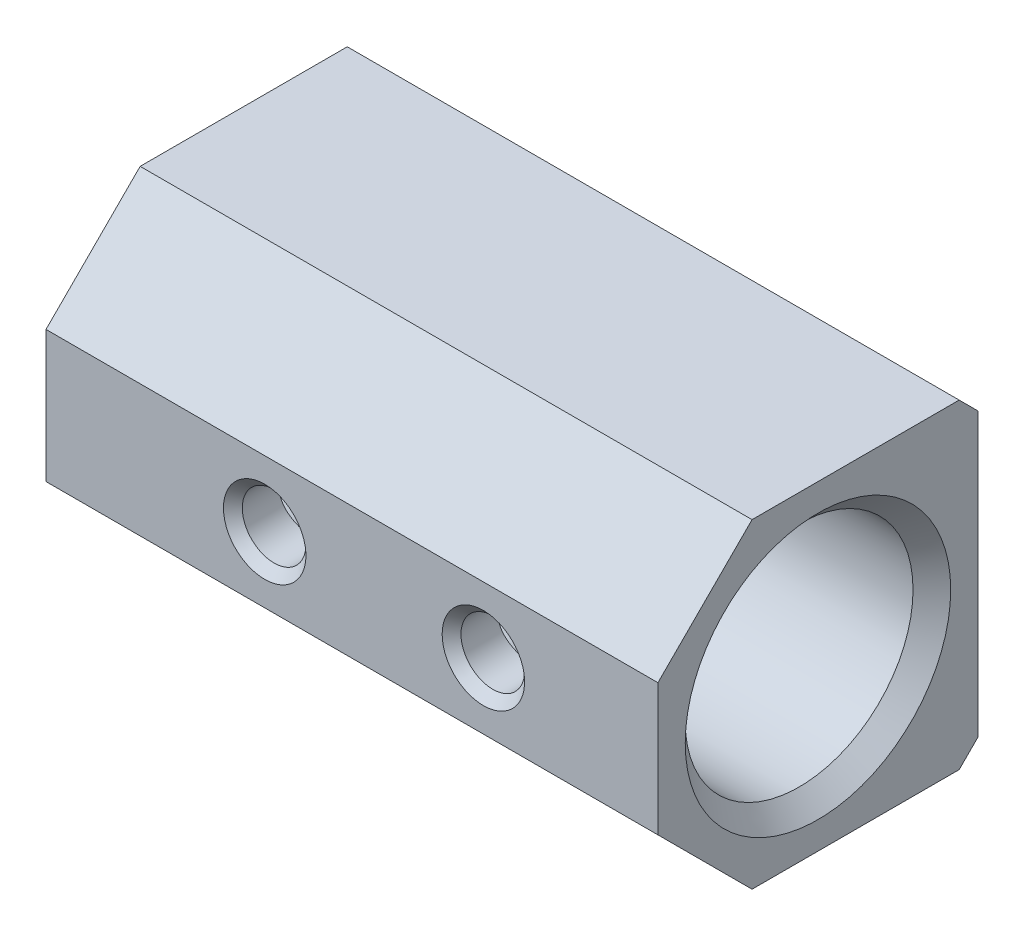
SolidWorks part; units mm, degrees
ref_plane "Front Plane" through (0, 0, 0) normal (0, 0, 1) x (1, 0, 0)
ref_plane "Top Plane" through (0, 0, 0) normal (0, 1, 0) x (1, 0, 0)
ref_plane "Right Plane" through (0, 0, 0) normal (1, 0, 0) x (0, 0, -1)
sketch "Sketch2" plane through (0, 0, 0) normal (0, 0, 1) x (1, 0, 0)
  line L1 (-32.5, -17) -> (32.5, -17)
  line L2 (-32.5, -17) -> (-32.5, 17)
  line L3 (-32.5, 17) -> (32.5, 17)
  line L4 (32.5, -17) -> (32.5, 17)
  line L5 (-32.5, -17) -> (32.5, 17) construction
  line L6 (-32.5, 17) -> (32.5, -17) construction
  point P0 (0, 0)
  dimension "D1" = 34
  dimension "D2" = 65
extrude "Boss-Extrude1" add sketch "Sketch2" along normal blind 34
chamfer "Chamfer1" distance 10 angle 45 2 edges at (0, 17, 34) (0, -17, 34)
chamfer "Chamfer2" distance 2 angle 45 2 edges at (0, 17, 0) (0, -17, 0)
sketch "Sketch3" plane through (32.5, 0, 0) normal (1, 0, 0) x (0, 0, -1)
  line L0 (0, -15) -> (0, 15) construction
  line L1 (-24, 17) -> (-2, 17) construction
  circle A0 centre (-17, 0) radius 12.1
  dimension "D1" = 24.2
  dimension "D2" = 17
  dimension "D3" = 17
extrude "Cut-Extrude1" cut sketch "Sketch3" against normal through all
chamfer "Chamfer3" distance 2 angle 45 1 edges at (32.5, 0, 4.9)
sketch "Sketch4" plane through (0, 0, 34) normal (0, 0, 1) x (1, 0, 0)
  line L0 (-32.5, 7) -> (-32.5, -7) construction
  circle A0 centre (-9.27, 0) radius 3.38
  circle A1 centre (13.96, 0) radius 3.38
  point P6 (0, 0)
  point P8 (0, 0)
  dimension "D2" = 6.76
  dimension "D1" = 23.23
  dimension "D3" = 23.23
extrude "Cut-Extrude2" cut sketch "Sketch4" against normal through all
chamfer "Chamfer4" distance 1 angle 45 4 edges at (17.34, 0, 34) (-5.89, 0, 34) (-5.89, 0, 0) (17.34, 0, 0)
